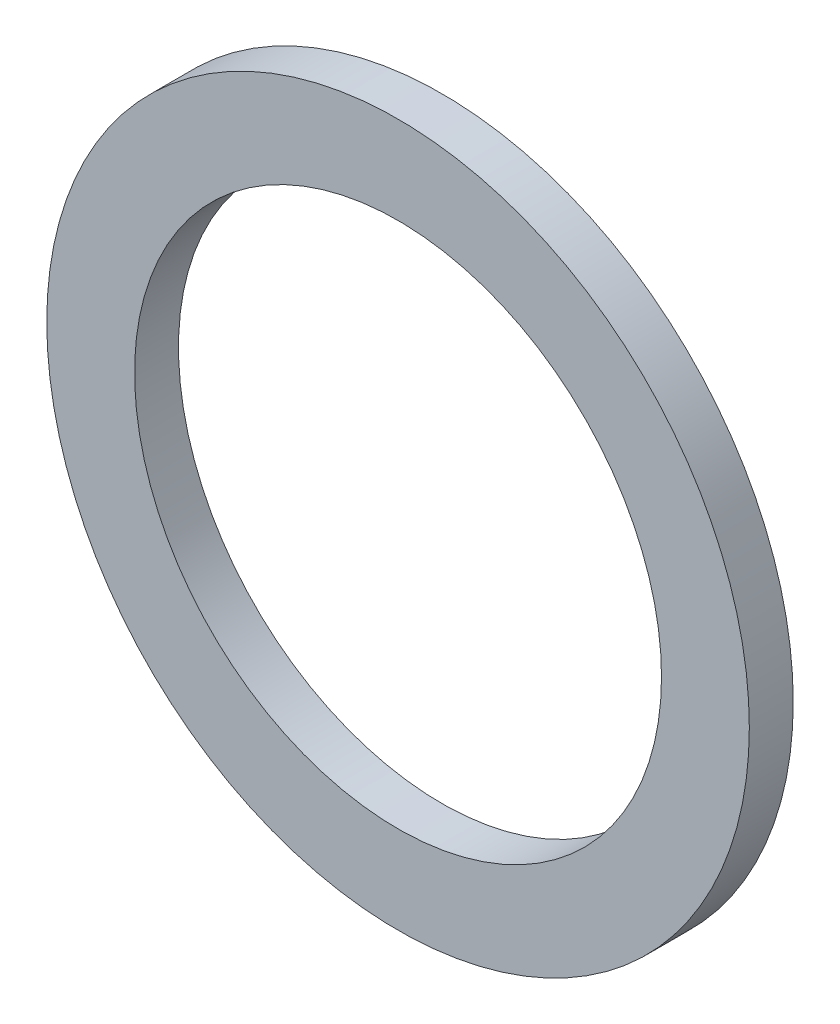
SolidWorks part; units mm, degrees
material "AISI 304"
ref_plane "前视基准面" through (0, 0, 0) normal (0, 0, 1) x (1, 0, 0)
ref_plane "上视基准面" through (0, 0, 0) normal (0, 1, 0) x (1, 0, 0)
ref_plane "右视基准面" through (0, 0, 0) normal (1, 0, 0) x (0, 0, -1)
other "Configuration Table"
sketch "草图1" plane through (0, 0, 0) normal (0, 0, 1) x (1, 0, 0)
  circle A0 centre (0, 0) radius 8
  circle A1 centre (0, 0) radius 6
  dimension "D1" = 16
  dimension "D2" = 12
extrude "凸台-拉伸1" add sketch "草图1" along normal blind 1
